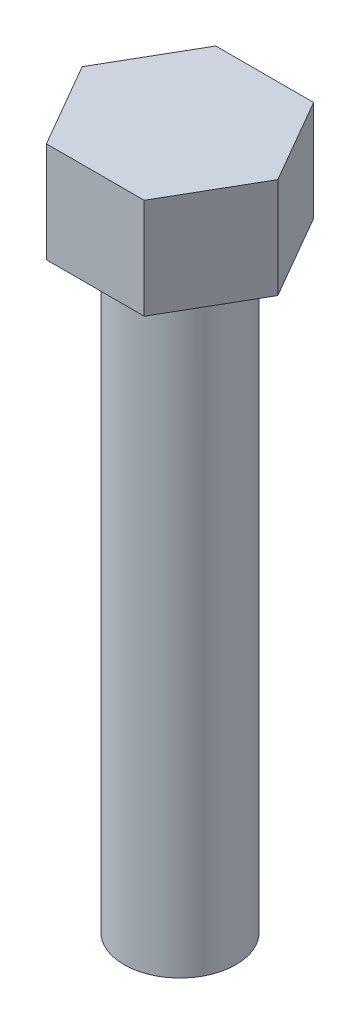
SolidWorks part; units mm, degrees
ref_plane "Front Plane" through (0, 0, 0) normal (0, 0, 1) x (1, 0, 0)
ref_plane "Top Plane" through (0, 0, 0) normal (0, 1, 0) x (1, 0, 0)
ref_plane "Right Plane" through (0, 0, 0) normal (1, 0, 0) x (0, 0, -1)
sketch "Sketch1" plane through (0, 0, 0) normal (0, 1, 0) x (1, 0, 0)
  line L0 (-2.3375, -4.0487) -> (2.3375, -4.0487)
  line L1 (2.3375, -4.0487) -> (4.675, 0)
  line L2 (4.675, 0) -> (2.3375, 4.0487)
  line L3 (2.3375, 4.0487) -> (-2.3375, 4.0487)
  line L4 (-2.3375, 4.0487) -> (-4.675, 0)
  line L5 (-4.675, 0) -> (-2.3375, -4.0487)
  circle A0 centre (0, 0) radius 2.675
sketch "Sketch2" plane through (0, 0, 0) normal (0, 1, 0) x (1, 0, 0)
  line L0 (-2.3375, 4.0487) -> (-4.675, 0) construction
  line L1 (-4.675, 0) -> (-2.3375, -4.0487) construction
  line L2 (-2.3375, -4.0487) -> (2.3375, -4.0487) construction
  line L3 (2.3375, -4.0487) -> (4.675, 0) construction
  line L4 (4.675, 0) -> (2.3375, 4.0487) construction
  line L5 (2.3375, 4.0487) -> (-2.3375, 4.0487) construction
  line L6 (-2.3375, 4.0487) -> (-4.675, 0)
  line L7 (-4.675, 0) -> (-2.3375, -4.0487)
  line L8 (-2.3375, -4.0487) -> (2.3375, -4.0487)
  line L9 (2.3375, -4.0487) -> (4.675, 0)
  line L10 (4.675, 0) -> (2.3375, 4.0487)
  line L11 (2.3375, 4.0487) -> (-2.3375, 4.0487)
extrude "Boss-Extrude1" add sketch "Sketch2" along normal blind 4.8
sketch "Sketch3" plane through (0, 0, 0) normal (0, -1, 0) x (1, 0, 0)
  circle A0 centre (0, 0) radius 2.675 construction
  circle A1 centre (0, 0) radius 2.675
extrude "Boss-Extrude2" add sketch "Sketch3" along normal blind 28.7
fillet "Fillet1" radius 0.25 1 edges at (0, 0, -2.675)
